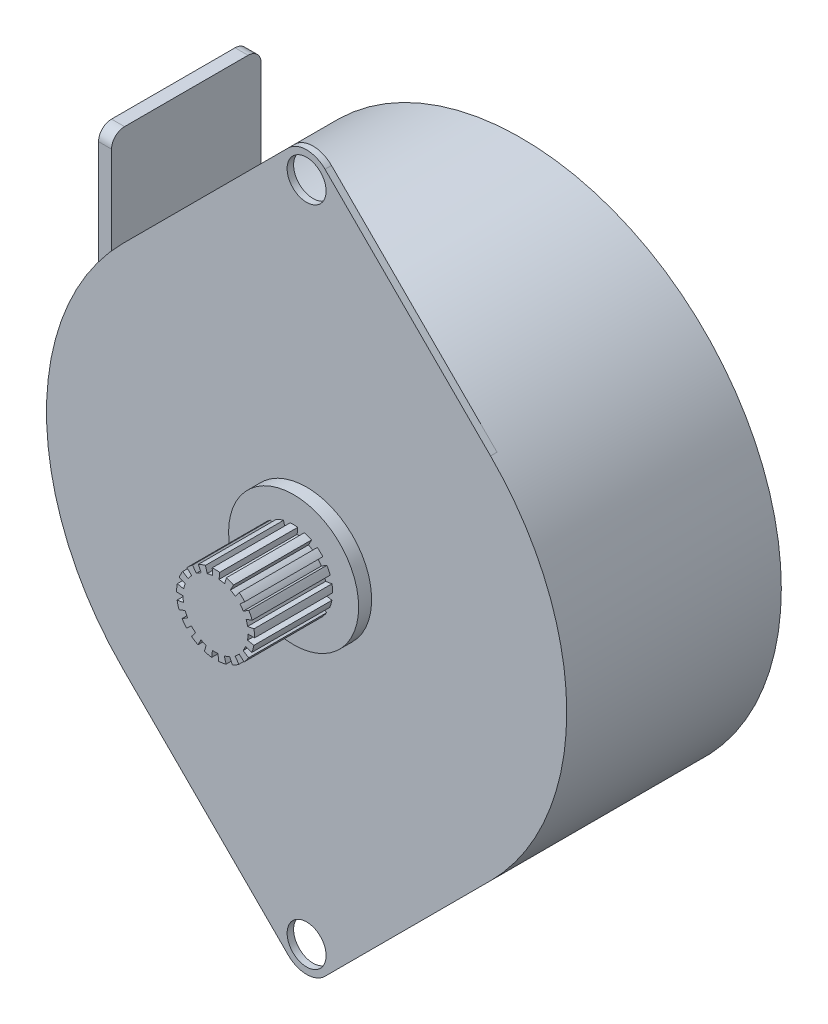
SolidWorks part; units mm, degrees
ref_plane "Front Plane" through (0, 0, 0) normal (0, 0, 1) x (1, 0, 0)
ref_plane "Top Plane" through (0, 0, 0) normal (0, 1, 0) x (1, 0, 0)
ref_plane "Right Plane" through (0, 0, 0) normal (1, 0, 0) x (0, 0, -1)
sketch "Sketch1" plane through (0, 0, 0) normal (0, 0, 1) x (1, 0, 0)
  line L0 (0, 89.3734) -> (0, -82.1676) construction
  line L1 (-104.619, 0) -> (112.9281, 0) construction
  circle A0 centre (0, 0) radius 20
extrude "Boss-Extrude1" add sketch "Sketch1" against normal blind 16
sketch "Sketch3" plane through (0, 0, 0) normal (0, 0, 1) x (1, 0, 0)
  line L0 (0, 24.5735) -> (0, -24.2927) construction
  line L1 (-38.0819, 0) -> (32.259, 0) construction
  line L2 (0, 0) -> (-22.7086, 22.7086) construction
  line L3 (-22.7086, 22.7086) -> (17.8671, -17.8671) construction
  line L4 (0, 0) -> (22.7086, 22.7086) construction
  line L5 (22.7086, 22.7086) -> (-20.4499, -20.4499) construction
  line L6 (-14.1421, 14.1421) -> (-1.4142, 26.8701)
  line L7 (1.4142, 26.8701) -> (14.1421, 14.1421)
  line L8 (-14.1421, -14.1421) -> (-1.4142, -26.8701)
  line L9 (1.4142, -26.8701) -> (14.1421, -14.1421)
  circle A0 centre (0, 0) radius 20 construction
  arc A1 (-14.1421, -14.1421) -> (-14.1421, 14.1421) centre (0, 0) cw
  arc A2 (14.1421, 14.1421) -> (14.1421, -14.1421) centre (0, 0) cw
  arc A3 (1.4142, 26.8701) -> (-1.4142, 26.8701) centre (0, 25.4558) ccw
  arc A4 (-1.4142, -26.8701) -> (1.4142, -26.8701) centre (0, -25.4558) ccw
  circle A5 centre (0, -25.4558) radius 1.5
  circle A6 centre (0, 25.4558) radius 1.5
  dimension "D1" = 2
extrude "Boss-Extrude3" add sketch "Sketch3" along normal blind 0.5
sketch "Sketch4" plane through (0, 0, 0.5) normal (0, 0, 1) x (1, 0, 0)
  line L0 (-37.3351, 0) -> (31.6681, 0) construction
  line L1 (0, 29.8764) -> (0, -31.2098) construction
  circle A0 centre (0, 0) radius 5
  dimension "D1" = 10
extrude "Boss-Extrude4" add sketch "Sketch4" along normal blind 1
sketch "Sketch5" plane through (0, 0, 1.5) normal (0, 0, 1) x (1, 0, 0)
  line L0 (0, 11.1573) -> (0, -10.5871) construction
  line L1 (-13.0529, 0) -> (9.403, 0) construction
  circle A0 centre (0, 0) radius 3
extrude "Boss-Extrude5" add sketch "Sketch5" along normal blind 6
sketch "Sketch6" plane through (0, 0, 7.5) normal (0, 0, 1) x (1, 0, 0)
  line L0 (0, 3.5953) -> (0, -3.6437) construction
  line L1 (-3.5694, 0) -> (3.3265, 0) construction
  line L2 (-2.4642, -0.4217) -> (-2.957, -0.5061)
  line L3 (-2.5, 0.0126) -> (-3, 0.0151)
  line L4 (-2.4501, 0.4969) -> (-2.9401, 0.5963)
  line L5 (-2.3266, 0.9148) -> (-2.7919, 1.0978)
  line L6 (-2.1454, -1.2834) -> (-2.5745, -1.5401)
  line L7 (-2.3357, -0.8914) -> (-2.8028, -1.0696)
  line L8 (-2.1052, 1.3484) -> (-2.5262, 1.6181)
  line L9 (-1.839, 1.6935) -> (-2.2068, 2.0322)
  line L10 (-1.4759, 2.0179) -> (-1.7711, 2.4214)
  line L11 (-1.1031, 2.2435) -> (-1.3237, 2.6922)
  line L12 (-0.6473, 2.4147) -> (-0.7768, 2.8977)
  line L13 (-0.2181, 2.4905) -> (-0.2618, 2.9886)
  line L14 (0.2687, 2.4855) -> (0.3225, 2.9826)
  line L15 (0.6962, 2.4011) -> (0.8355, 2.8813)
  line L16 (1.1484, 2.2206) -> (1.3781, 2.6647)
  line L17 (1.5166, 1.9874) -> (1.8199, 2.3849)
  line L18 (1.8731, 1.6558) -> (2.2477, 1.9869)
  line L19 (2.1321, 1.3054) -> (2.5586, 1.5664)
  line L20 (2.3447, 0.8673) -> (2.8137, 1.0408)
  line L21 (2.4597, 0.447) -> (2.9517, 0.5364)
  line L22 (2.4997, -0.0382) -> (2.9996, -0.0459)
  line L23 (2.4551, -0.4717) -> (2.9461, -0.5661)
  line L24 (2.3171, -0.9387) -> (2.7805, -1.1264)
  line L25 (2.1189, -1.3268) -> (2.5427, -1.5921)
  line L26 (1.8215, -1.7123) -> (2.1859, -2.0548)
  line L27 (1.4965, -2.0026) -> (1.7958, -2.4031)
  line L28 (1.08, -2.2547) -> (1.296, -2.7056)
  line L29 (0.6721, -2.408) -> (0.8065, -2.8896)
  line L30 (0.1926, -2.4926) -> (0.2311, -2.9911)
  line L31 (-0.2432, -2.4881) -> (-0.2918, -2.9858)
  line L32 (-0.7209, -2.3938) -> (-0.865, -2.8726)
  line L33 (-1.1256, -2.2323) -> (-1.3507, -2.6787)
  line L34 (-1.5369, -1.9718) -> (-1.8443, -2.3661)
  line L35 (-1.856, -1.6749) -> (-2.2272, -2.0099)
  arc A0 (-2.5, 0.0126) -> (-2.4642, -0.4217) centre (0, 0) ccw
  circle A1 centre (0, 0) radius 3 construction
  arc A2 (-3, 0.0151) -> (-2.957, -0.5061) centre (0, 0) ccw
  arc A3 (-2.3357, -0.8914) -> (-2.1454, -1.2834) centre (0, 0) ccw
  arc A4 (-2.8028, -1.0696) -> (-2.5745, -1.5401) centre (0, 0) ccw
  arc A5 (-2.3266, 0.9148) -> (-2.4501, 0.4969) centre (0, 0) ccw
  arc A6 (-2.7919, 1.0978) -> (-2.9401, 0.5963) centre (0, 0) ccw
  arc A7 (-1.839, 1.6935) -> (-2.1052, 1.3484) centre (0, 0) ccw
  arc A8 (-2.2068, 2.0322) -> (-2.5262, 1.6181) centre (0, 0) ccw
  arc A9 (-1.1031, 2.2435) -> (-1.4759, 2.0179) centre (0, 0) ccw
  arc A10 (-1.3237, 2.6922) -> (-1.7711, 2.4214) centre (0, 0) ccw
  arc A11 (-0.2181, 2.4905) -> (-0.6473, 2.4147) centre (0, 0) ccw
  arc A12 (-0.2618, 2.9886) -> (-0.7768, 2.8977) centre (0, 0) ccw
  arc A13 (0.6962, 2.4011) -> (0.2687, 2.4855) centre (0, 0) ccw
  arc A14 (0.8355, 2.8813) -> (0.3225, 2.9826) centre (0, 0) ccw
  arc A15 (1.5166, 1.9874) -> (1.1484, 2.2206) centre (0, 0) ccw
  arc A16 (1.8199, 2.3849) -> (1.3781, 2.6647) centre (0, 0) ccw
  arc A17 (2.1321, 1.3054) -> (1.8731, 1.6558) centre (0, 0) ccw
  arc A18 (2.5586, 1.5664) -> (2.2477, 1.9869) centre (0, 0) ccw
  arc A19 (2.4597, 0.447) -> (2.3447, 0.8673) centre (0, 0) ccw
  arc A20 (2.9517, 0.5364) -> (2.8137, 1.0408) centre (0, 0) ccw
  arc A21 (2.4551, -0.4717) -> (2.4997, -0.0382) centre (0, 0) ccw
  arc A22 (2.9461, -0.5661) -> (2.9996, -0.0459) centre (0, 0) ccw
  arc A23 (2.1189, -1.3268) -> (2.3171, -0.9387) centre (0, 0) ccw
  arc A24 (2.5427, -1.5921) -> (2.7805, -1.1264) centre (0, 0) ccw
  arc A25 (1.4965, -2.0026) -> (1.8215, -1.7123) centre (0, 0) ccw
  arc A26 (1.7958, -2.4031) -> (2.1859, -2.0548) centre (0, 0) ccw
  arc A27 (0.6721, -2.408) -> (1.08, -2.2547) centre (0, 0) ccw
  arc A28 (0.8065, -2.8896) -> (1.296, -2.7056) centre (0, 0) ccw
  arc A29 (-0.2432, -2.4881) -> (0.1926, -2.4926) centre (0, 0) ccw
  arc A30 (-0.2918, -2.9858) -> (0.2311, -2.9911) centre (0, 0) ccw
  arc A31 (-1.1256, -2.2323) -> (-0.7209, -2.3938) centre (0, 0) ccw
  arc A32 (-1.3507, -2.6787) -> (-0.865, -2.8726) centre (0, 0) ccw
  arc A33 (-1.856, -1.6749) -> (-1.5369, -1.9718) centre (0, 0) ccw
  arc A34 (-2.2272, -2.0099) -> (-1.8443, -2.3661) centre (0, 0) ccw
  point P78 (0, 0)
  dimension "D2" = 0.5
  dimension "D1" = 10
  dimension "D3" = 17
extrude "Cut-Extrude1" cut sketch "Sketch6" against normal up to surface (6 mm away) up to face at (5, 0, 1.5)
ref_plane "Plane1" through (-20, 0, 0) normal (-1, 0, 0) x (0, 0, 1)
sketch "Sketch8" plane through (-20, 0, 0) normal (-1, 0, 0) x (0, 0, 1)
  line L0 (-31.6963, 0) -> (18.0268, 0) construction
  line L1 (-16, 20) -> (-16, -20) construction
  line L2 (-16, 16) -> (-4.5, 16)
  line L3 (-16, 16) -> (-16, -7)
  line L4 (-16, -7) -> (-4.5, -7)
  line L5 (-4.5, 16) -> (-4.5, -7)
  line L6 (0.5, -14.1421) -> (0.5, 14.1421) construction
  dimension "D1" = 5
  dimension "D2" = 7
  dimension "D3" = 16
extrude "Boss-Extrude6" add sketch "Sketch8" along normal blind 1 separate body
fillet "Fillet1" radius 1 4 edges at (-20.5, -7, -16) (-20.5, -7, -4.5) (-20.5, 16, -4.5) (-20.5, 16, -16)
